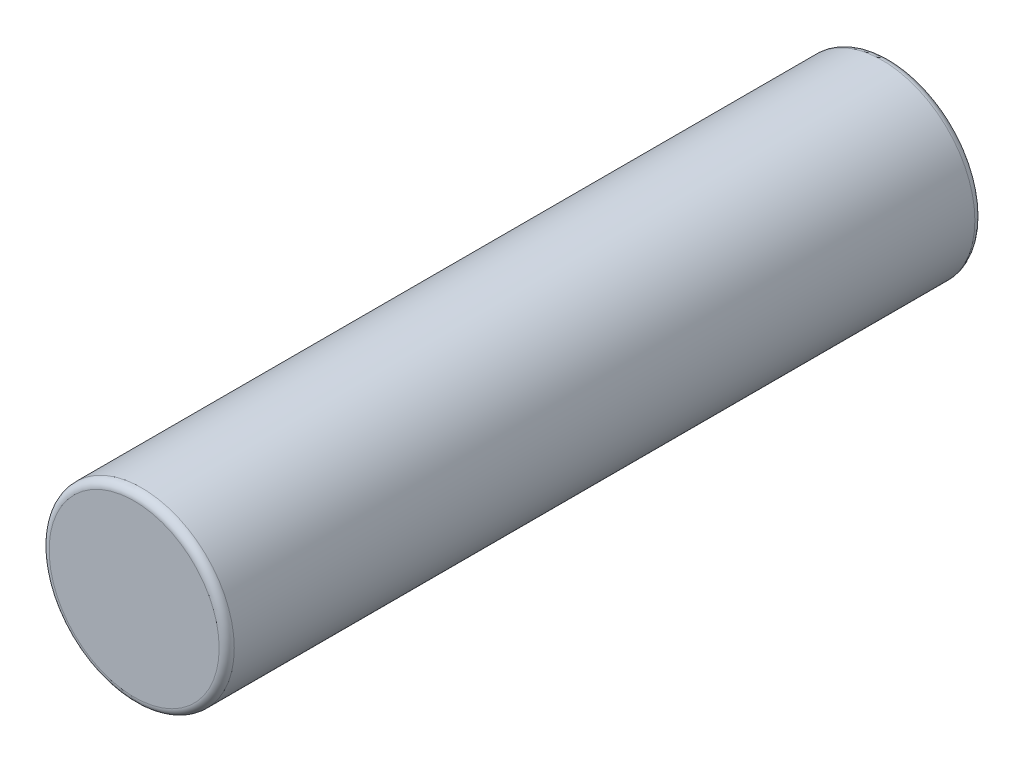
SolidWorks part; units mm, degrees
ref_plane "Front Plane" through (0, 0, 0) normal (0, 0, 1) x (1, 0, 0)
ref_plane "Top Plane" through (0, 0, 0) normal (0, 1, 0) x (1, 0, 0)
ref_plane "Right Plane" through (0, 0, 0) normal (1, 0, 0) x (0, 0, -1)
sketch "Croquis1" plane through (0, 0, 0) normal (0, 0, 1) x (1, 0, 0)
  circle A0 centre (0, 0) radius 2.45
  dimension "D1" = 4.9
extrude "Saliente-Extruir1" add sketch "Croquis1" along normal blind 20
fillet "Redondeo1" radius 0.2 2 edges at (2.45, 0, 0) (2.45, 0, 20)
